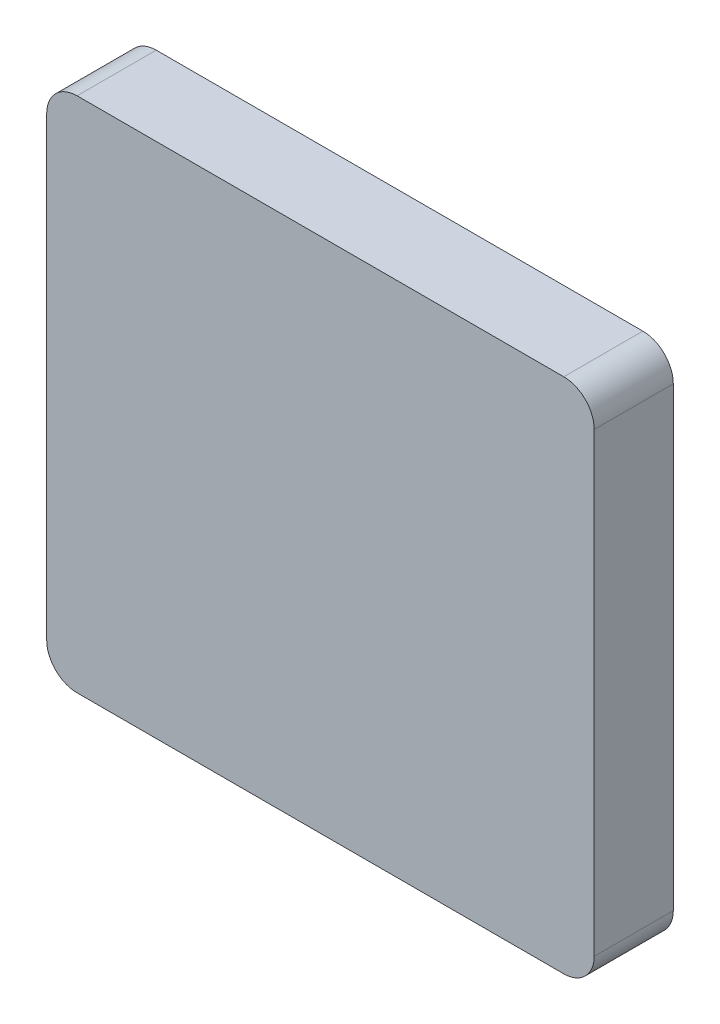
SolidWorks part; units mm, degrees
ref_plane "正面" through (0, 0, 0) normal (0, 0, 1) x (1, 0, 0)
ref_plane "平面" through (0, 0, 0) normal (0, 1, 0) x (1, 0, 0)
ref_plane "右側面" through (0, 0, 0) normal (1, 0, 0) x (0, 0, -1)
sketch "ｽｹｯﾁ1" plane through (0, 0, 0) normal (0, 0, 1) x (1, 0, 0)
  line L1 (9, 8.5) -> (-9, 8.5)
  line L2 (9, 8.5) -> (9, -8.5)
  line L3 (9, -8.5) -> (-9, -8.5)
  line L4 (-9, 8.5) -> (-9, -8.5)
  line L5 (9, 8.5) -> (-9, -8.5) construction
  line L6 (9, -8.5) -> (-9, 8.5) construction
  point P0 (0, 0)
  dimension "D1" = 18
  dimension "D2" = 17
extrude "ﾎﾞｽ - 押し出し1" add sketch "ｽｹｯﾁ1" along normal blind 2.6
fillet "ﾌｨﾚｯﾄ2" radius 1 4 edges at (-9, -8.5, 1.3) (9, -8.5, 1.3) (9, 8.5, 1.3) (-9, 8.5, 1.3)
